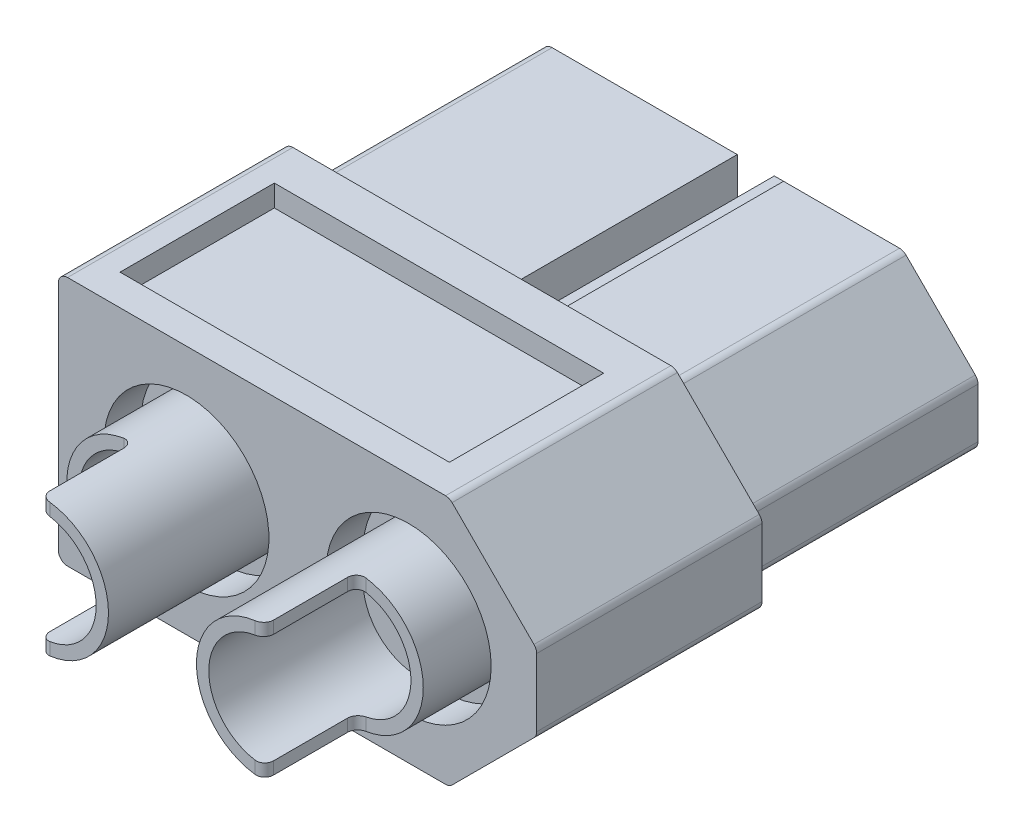
SolidWorks part; units mm, degrees
material "PVC 0.007 Plasticized"
ref_plane "Спереди" through (0, 0, 0) normal (0, 0, 1) x (1, 0, 0)
ref_plane "Сверху" through (0, 0, 0) normal (0, 1, 0) x (1, 0, 0)
ref_plane "Справа" through (0, 0, 0) normal (1, 0, 0) x (0, 0, -1)
sketch "Эскиз1" plane through (0, 0, 0) normal (0, 0, 1) x (1, 0, 0)
  line L0 (4.9216, 4.05) -> (7.75, 1.2216)
  line L1 (-7.75, 4.05) -> (7.75, 4.05)
  line L2 (-7.75, 4.05) -> (-7.75, -4.05)
  line L3 (-7.75, -4.05) -> (7.75, -4.05)
  line L4 (7.75, 4.05) -> (7.75, -4.05)
  line L5 (-7.75, 4.05) -> (7.75, -4.05) construction
  line L6 (-7.75, -4.05) -> (7.75, 4.05) construction
  line L7 (0, 0) -> (7.75, 0) construction
  line L8 (4.9216, -4.05) -> (7.75, -1.2216)
  point P0 (0, 0)
  dimension "D1" = 8.1
  dimension "D2" = 15.5
  dimension "D3" = 45
  dimension "D4" = 4
extrude "Бобышка-Вытянуть1" add sketch "Эскиз1" along normal blind 15 contours L3 L8 L4 L0 L1 L2
sketch "Эскиз2" plane through (0, 0, 0) normal (0, 0, -1) x (-1, 0, 0)
  line L12 (-4.6316, -3.35) -> (7.05, -3.35)
  line L13 (7.05, -3.35) -> (7.05, 3.35)
  line L14 (7.05, 3.35) -> (-4.6316, 3.35)
  line L15 (-4.6316, 3.35) -> (-7.05, 0.9316)
  line L16 (-7.05, 0.9316) -> (-7.05, -0.9316)
  line L17 (-7.05, -0.9316) -> (-4.6316, -3.35)
  line L18 (-4.6316, -3.35) -> (7.05, -3.35)
  line L19 (7.05, -3.35) -> (7.05, 3.35)
  line L20 (7.05, 3.35) -> (-4.6316, 3.35)
  line L21 (-4.6316, 3.35) -> (-7.05, 0.9316)
  line L22 (-7.05, 0.9316) -> (-7.05, -0.9316)
  line L23 (-7.05, -0.9316) -> (-4.6316, -3.35)
  line M7 (-4.9216, -4.05) -> (7.75, -4.05)
  line M8 (7.75, -4.05) -> (7.75, 4.05)
  line M9 (7.75, 4.05) -> (-4.9216, 4.05)
  line M10 (-4.9216, 4.05) -> (-7.75, 1.2216)
  line M11 (-7.75, 1.2216) -> (-7.75, -1.2216)
  line M12 (-7.75, -1.2216) -> (-4.9216, -4.05)
  dimension "D1" = 0.7
extrude "Вырез-Вытянуть1" cut sketch "Эскиз2" against normal blind 7.7 contours L23 L22 L21 L20 L19 L18 M12 M7 M8 M9 M10 M11
sketch "Эскиз13" plane through (0, 0, 0) normal (0, 0, -1) x (-1, 0, 0)
  line L0 (0, 0) -> (0, 1.988) construction
  circle A0 centre (-3.6, 0) radius 2.175
  circle A1 centre (3.6, 0) radius 2.175
  dimension "D1" = 4.35
  dimension "D2" = 7.2
extrude "Вырез-Вытянуть9" cut sketch "Эскиз13" against normal blind 7.7
ref_plane "Плоскость1" through (0, 0, 1.5) normal (0, 0, -1) x (-1, 0, 0)
sketch "Эскиз3" plane through (0, 0, 1.5) normal (0, 0, -1) x (-1, 0, 0)
  line L1 (7.05, 3.35) -> (-4.6316, 3.35) construction
  line L2 (-0.75, 2.15) -> (0.75, 2.15)
  line L3 (-0.75, 2.15) -> (-0.75, 3.35)
  line L4 (-0.75, 3.35) -> (0.75, 3.35)
  line L5 (0.75, 2.15) -> (0.75, 3.35)
  line L6 (-0.75, 2.15) -> (0.75, 3.35) construction
  line L7 (-0.75, 3.35) -> (0.75, 2.15) construction
  point P1 (0, 2.75)
  dimension "D1" = 1.2
  dimension "D2" = 1.5
extrude "Вырез-Вытянуть10" cut sketch "Эскиз3" against normal up to surface and the other way up to surface up to face at (1.5439, 0, 7.7) other way up to face at (1.425, 0, 0)
sketch "Эскиз14" plane through (0, 0, 0) normal (0, 0, -1) x (-1, 0, 0)
  line L1 (-0.75, 2.15) -> (0.75, 2.15)
  line L2 (-0.75, 2.15) -> (-0.75, -1.85)
  line L3 (-0.75, -1.85) -> (0.75, -1.85)
  line L4 (0.75, 2.15) -> (0.75, -1.85)
  dimension "D1" = 4
  dimension "D2" = 1.5
extrude "Бобышка-Вытянуть5" add sketch "Эскиз14" along normal blind 1.2
sketch "Эскиз5" plane through (0, 0, 7.7) normal (0, 0, -1) x (-1, 0, 0)
  line L0 (0, 0) -> (0, -2.5029) construction
  circle A0 centre (3.6, 0) radius 2.175
  circle A1 centre (-3.6, 0) radius 2.175
  dimension "D1" = 4.35
  dimension "D2" = 7.2
extrude "Бобышка-Вытянуть3" add sketch "Эскиз5" along normal offset from surface 1.2 and the other way offset from surface (12 mm away) 4.7 up to face at (-1.425, 0, 0) other way up to face at (1.6405, 0, 15)
sketch "Эскиз6" plane through (0, 0, 15) normal (0, 0, 1) x (1, 0, 0)
  line L0 (0, 0) -> (0, -1.6207) construction
  circle A0 centre (3.6, 0) radius 2.175
  circle A1 centre (3.6, 0) radius 2.675
  circle A3 centre (3.6, 0) radius 2.175 construction
  circle A4 centre (-3.6, 0) radius 2.675
  circle A5 centre (-3.6, 0) radius 2.175
  dimension "D1" = 0.5
extrude "Вырез-Вытянуть3" cut sketch "Эскиз6" against normal blind 1.2
sketch "Эскиз7" plane through (0, 0, 19.7) normal (0, 0, 1) x (1, 0, 0)
  line L0 (0, 0) -> (0, 2.5309) construction
  circle A0 centre (-3.6, 0) radius 1.775
  circle A1 centre (-3.6, 0) radius 2.175 construction
  circle A2 centre (3.6, 0) radius 1.775
  dimension "D1" = 0.4
extrude "Вырез-Вытянуть4" cut sketch "Эскиз7" against normal blind 5
sketch "Эскиз8" plane through (0, 0, 0) normal (0, 1, 0) x (1, 0, 0)
  line L0 (0, 0) -> (0, -21.1053) construction
  line L1 (3.625, -19.7) -> (3.625, -16.7)
  line L2 (-5.775, -19.7) -> (-3.625, -19.7)
  line L3 (-5.775, -19.7) -> (-5.775, -16.7)
  line L4 (-5.775, -16.7) -> (-3.625, -16.7)
  line L5 (-3.625, -19.7) -> (-3.625, -16.7)
  line L6 (5.775, -16.7) -> (3.625, -16.7)
  line L7 (5.775, -19.7) -> (5.775, -16.7)
  line L8 (5.775, -19.7) -> (3.625, -19.7)
  dimension "D1" = 3
  dimension "D2" = 2.15
extrude "Вырез-Вытянуть5" cut sketch "Эскиз8" against normal through all both and the other way through all
sketch "Эскиз10" plane through (0, 0, 1.2) normal (0, 0, -1) x (-1, 0, 0)
  line L0 (0, 0) -> (0, 1.4291) construction
  circle A8 centre (-3.6, 0) radius 2.15
  circle A9 centre (3.6, 0) radius 2.15
  dimension "D1" = 4.3
extrude "Вырез-Вытянуть7" cut sketch "Эскиз10" against normal up to surface (6.5 mm away) up to face at (0.9263, 1.1, 7.7)
fillet "Скругление2" radius 0.3 8 edges at (3.625, 1.9748, 16.7) (3.625, -1.9748, 16.7) (-3.625, -1.9748, 16.7) (-3.625, 1.9748, 16.7) (3.625, 1.9748, 19.7) (3.625, -1.9748, 19.7) (-3.625, -1.9748, 19.7) (-3.625, 1.9748, 19.7)
sketch "Эскиз11" plane through (0, 4.05, 0) normal (0, 1, 0) x (1, 0, 0)
  line L0 (-7.75, -15) -> (-7.75, -7.7) construction
  line L1 (-6.75, -14) -> (3.9216, -14)
  line L2 (-6.75, -14) -> (-6.75, -9)
  line L3 (-6.75, -9) -> (3.9216, -9)
  line L4 (3.9216, -14) -> (3.9216, -9)
  line L5 (-7.75, -15) -> (4.9216, -15) construction
  line L6 (4.9216, -15) -> (4.9216, -7.7) construction
  dimension "D1" = 1
  dimension "D2" = 1
  dimension "D3" = 1
  dimension "D4" = 5
extrude "Вырез-Вытянуть8" cut sketch "Эскиз11" against normal blind 0.7
mirror "Зеркальное отражение1" about plane through (0, 0, 0) normal (0, 1, 0) of "Вырез-Вытянуть8"
sketch "Эскиз12" plane through (0, -3.35, 0) normal (0, -1, 0) x (1, 0, 0)
  line L0 (2.4216, 12.5) -> (-5.4393, 12.5) construction
  line L1 (-6.75, 14) -> (3.9216, 14) construction
  line L2 (3.9216, 14) -> (3.9216, 9) construction
  text T0 "XT-60" font "Arial" height 2
  dimension "D1" = 1.5
  dimension "D2" = 1.5
extrude "Бобышка-Вытянуть4" add sketch "Эскиз12" along normal blind 0.2
fillet "Скругление3" radius 0.3 12 edges at (-7.75, 4.05, 11.35) (-7.75, -4.05, 11.35) (4.9216, 4.05, 11.35) (7.75, 1.2216, 11.35) (7.75, -1.2216, 11.35) (4.9216, -4.05, 11.35) (4.6316, 3.35, 3.85) (-7.05, 3.35, 3.85) (-7.05, -3.35, 3.85) (7.05, 0.9316, 3.85) (7.05, -0.9316, 3.85) (4.6316, -3.35, 3.85)
sketch "Sketch1" plane through (0, 0, 15) normal (0, 0, 1) x (1, 0, 0)
  point P0 (3.6, 0)
  point P1 (-3.6, 0)
ref_plane "Plane1" through (0, 0, 21.35) normal (0, 0, 1) x (1, 0, 0)
sketch "Sketch2" plane through (0, 0, 21.35) normal (0, 0, 1) x (1, 0, 0)
  point P0 (3.6, 0)
  point P1 (-3.6, 0)
